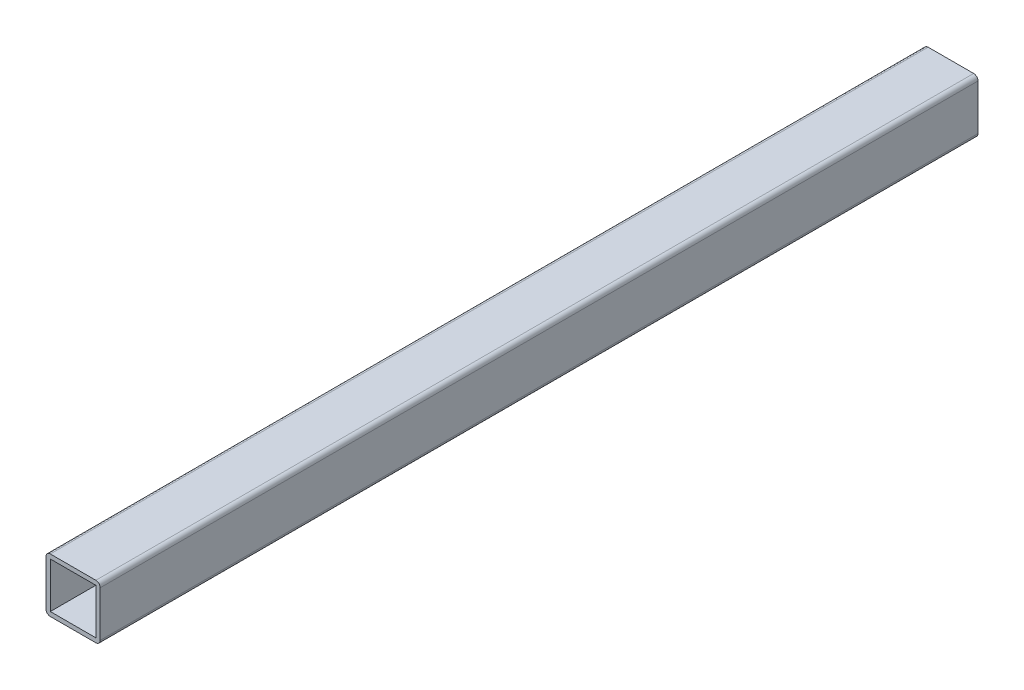
SolidWorks part; units mm, degrees
ref_plane "Спереди" through (0, 0, 0) normal (0, 0, 1) x (1, 0, 0)
ref_plane "Сверху" through (0, 0, 0) normal (0, 1, 0) x (1, 0, 0)
ref_plane "Справа" through (0, 0, 0) normal (1, 0, 0) x (0, 0, -1)
sketch "Эскиз1" plane through (0, 0, 0) normal (0, 0, 1) x (1, 0, 0)
  line L1 (4, 0) -> (46, 0)
  line L2 (0, 4) -> (0, 46)
  line L3 (4, 50) -> (46, 50)
  line L4 (50, 4) -> (50, 46)
  line L5 (4, 46) -> (46, 46)
  line L6 (4, 46) -> (4, 4)
  line L7 (4, 4) -> (46, 4)
  line L8 (46, 46) -> (46, 4)
  arc A0 (0, 46) -> (4, 50) centre (4, 46) cw
  arc A1 (4, 0) -> (0, 4) centre (4, 4) cw
  arc A2 (46, 0) -> (50, 4) centre (46, 4) ccw
  arc A3 (50, 46) -> (46, 50) centre (46, 46) ccw
  point P13 (0, 0)
  point P16 (50, 0)
  point P19 (50, 50)
  dimension "D7" = 4
  dimension "D1" = 50
  dimension "D2" = 50
  dimension "D3" = 4
  dimension "D4" = 4
  dimension "D5" = 4
  dimension "D6" = 4
extrude "Бобышка-Вытянуть1" add sketch "Эскиз1" along normal blind 810
